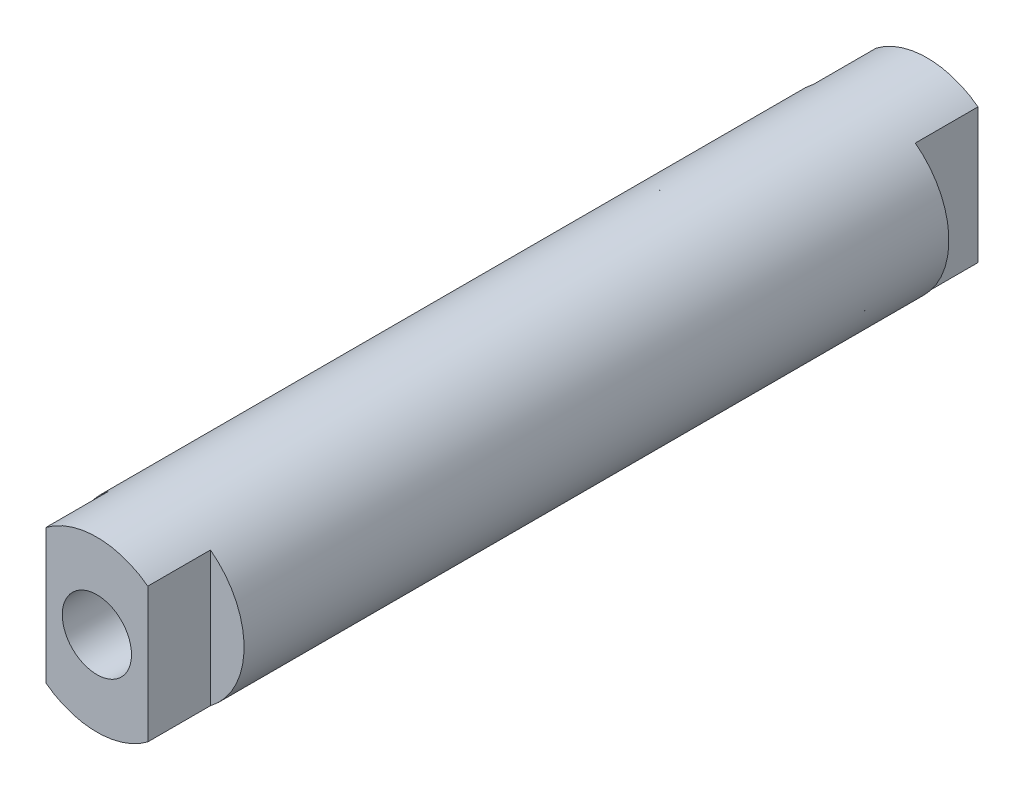
SolidWorks part; units mm, degrees
ref_plane "Front Plane" through (0, 0, 0) normal (0, 0, 1) x (1, 0, 0)
ref_plane "Top Plane" through (0, 0, 0) normal (0, 1, 0) x (1, 0, 0)
ref_plane "Right Plane" through (0, 0, 0) normal (1, 0, 0) x (0, 0, -1)
sketch "Sketch1" plane through (0, 0, 0) normal (0, 0, 1) x (1, 0, 0)
  circle A0 centre (0, 0) radius 10.9855
  dimension "D1" = 21.971
extrude "Boss-Extrude1" add sketch "Sketch1" along normal mid plane 107.95
sketch "Sketch2" plane through (0, 0, 53.975) normal (0, 0, 1) x (1, 0, 0)
  line L0 (-6.6167, 8.7693) -> (-6.6167, -8.7693)
  line L1 (-6.6167, -8.7693) -> (6.6167, -8.7693) construction
  line L2 (6.6167, -8.7693) -> (6.6167, 8.7693)
  arc A0 (6.6167, -8.7693) -> (6.6167, 8.7693) centre (0, 0) ccw
  circle A1 centre (0, 0) radius 10.9855
  arc A2 (-6.6167, 8.7693) -> (-6.6167, -8.7693) centre (0, 0) ccw
  dimension "D2" = 13.2334
  dimension "D1" = 0
extrude "Cut-Extrude1" cut sketch "Sketch2" against normal blind 8.1534
mirror "Mirror1" about plane through (0, 0, 0) normal (0, 0, 1) of "Cut-Extrude1"
sketch "Sketch3" plane through (0, 0, 45.8216) normal (0, 0, 1) x (1, 0, 0)
  circle A0 centre (0, 0) radius 9.525
  dimension "D1" = 19.05
extrude "Cut-Extrude2" cut sketch "Sketch3" against normal offset from surface (85.6432 mm away) 3 from offset 3 up to face at (-8.8011, 0, -45.8216) offset against normal yes
sketch "Sketch5" plane through (0, 0, 53.975) normal (0, 0, 1) x (1, 0, 0)
  circle A0 centre (0, 0) radius 4.5
  dimension "D1" = 9
extrude "Cut-Extrude3" cut sketch "Sketch5" against normal through all
